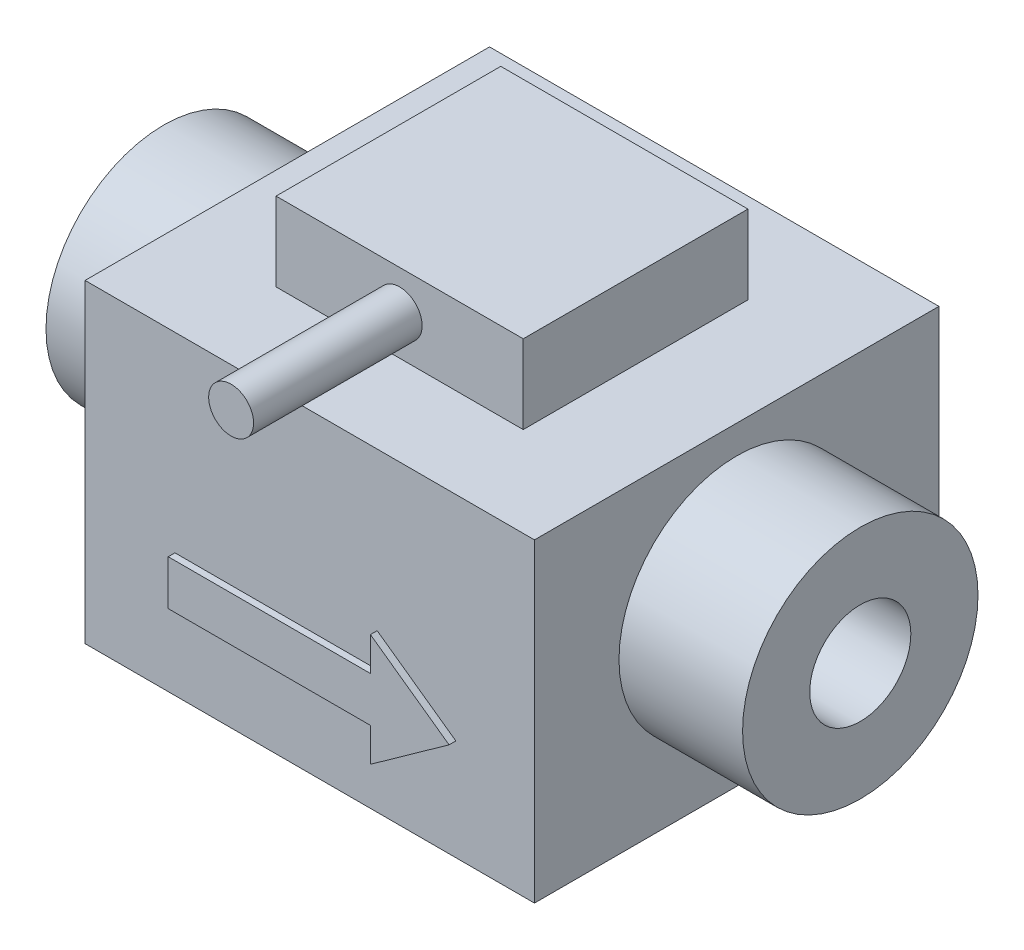
SolidWorks part; units mm, degrees
material "Nylon 6/10"
ref_plane "Front Plane" through (0, 0, 0) normal (0, 0, 1) x (1, 0, 0)
ref_plane "Top Plane" through (0, 0, 0) normal (0, 1, 0) x (1, 0, 0)
ref_plane "Right Plane" through (0, 0, 0) normal (1, 0, 0) x (0, 0, -1)
other "Configuration Table"
sketch "Sketch1" plane through (0, 0, 0) normal (0, 1, 0) x (1, 0, 0)
  line L1 (-20, -18) -> (20, -18)
  line L2 (-20, -18) -> (-20, 18)
  line L3 (-20, 18) -> (20, 18)
  line L4 (20, -18) -> (20, 18)
  line L5 (-20, -18) -> (20, 18) construction
  line L6 (-20, 18) -> (20, -18) construction
  point P6 (0, 0)
  dimension "D1" = 40
  dimension "D2" = 36
extrude "Body" add sketch "Sketch1" along normal blind 28
sketch "Sketch2" plane through (0, 0, 0) normal (0, 1, 0) x (1, 0, 0)
  line L0 (-11, -10) -> (11, -10)
  line L1 (11, -10) -> (11, 10)
  line L2 (11, 10) -> (-11, 10)
  line L3 (-11, 10) -> (-11, -10)
extrude "Sensor_Housing" add sketch "Sketch2" along normal blind 7 from offset 28
sketch "Sketch3" plane through (0, 0, 0) normal (1, 0, 0) x (0, 0, -1)
  circle A0 centre (0, 15) radius 10.4775
  dimension "D1" = 20.955
extrude "Inlet_Thread" add sketch "Sketch3" along normal blind 11 from offset 31
sketch "Sketch4" plane through (0, 0, 0) normal (1, 0, 0) x (0, 0, -1)
  circle A0 centre (0, 15) radius 10.4775
  dimension "D1" = 20.955
extrude "Outlet_Thread" add sketch "Sketch4" along normal blind 11 from offset 20
sketch "Sketch5" plane through (0, 0, 0) normal (1, 0, 0) x (0, 0, -1)
  circle A0 centre (0, 15) radius 4.5
  dimension "D1" = 9
extrude "Inlet_Bore" cut sketch "Sketch5" along normal blind 8 from offset 31
sketch "Sketch6" plane through (0, 0, 0) normal (1, 0, 0) x (0, 0, -1)
  circle A0 centre (0, 15) radius 4.5
  dimension "D1" = 9
extrude "Outlet_Bore" cut sketch "Sketch6" against normal blind 8 from offset 31
sketch "Sketch7" plane through (0, 0, 0) normal (0, 0, 1) x (1, 0, 0)
  circle A0 centre (0, 31.5) radius 2
  dimension "D1" = 4
extrude "Cable_Stub" add sketch "Sketch7" along normal blind 15 from offset 10
sketch "Sketch8" plane through (0, 0, 0) normal (0, 0, 1) x (1, 0, 0)
  line L0 (-12, 7) -> (6, 7)
  line L1 (6, 7) -> (6, 4)
  line L2 (6, 4) -> (13, 9)
  line L3 (13, 9) -> (6, 14)
  line L4 (6, 14) -> (6, 11)
  line L5 (6, 11) -> (-12, 11)
  line L6 (-12, 11) -> (-12, 7)
extrude "Flow_Arrow" add sketch "Sketch8" along normal blind 0.6 from offset 18
equation "\"Jar_OD\"= 90  'ASSUMED - Part G fallback - jar outer diameter"
equation "\"Jar_H\"= 120  'ASSUMED - Part G fallback - jar height"
equation "\"Pump_L\"= 45  'ASSUMED - Part G fallback"
equation "\"Pump_W\"= 24  'ASSUMED - Part G fallback"
equation "\"Pump_H\"= 33  'ASSUMED - Part G fallback"
equation "\"Pump_Outlet_OD\"= 7.5  'ASSUMED - Part G fallback"
equation "\"Tube_OD\"= 8  'ASSUMED - Part G fallback"
equation "\"Tube_ID\"= 6  'ASSUMED - Part G fallback"
equation "\"TDS_Body_Dia\"= 12  'ASSUMED - Part G fallback"
equation "\"TDS_Wet_Len\"= 45  'ASSUMED - Part G fallback - length in water"
equation "\"DS_Tube_Dia\"= 6  'ASSUMED - Part G fallback"
equation "\"DS_Tube_Len\"= 50  'ASSUMED - Part G fallback"
equation "\"ORP_Body_Dia\"= 12  'ASSUMED - Part G fallback"
equation "\"ORP_Body_Len\"= 150  'ASSUMED - Part G fallback"
equation "\"ORP_Cap_Dia\"= 16  'ASSUMED - Part G fallback"
equation "\"Turb_W\"= 33  'ASSUMED - Part G fallback - head width"
equation "\"Turb_D\"= 28  'ASSUMED - Part G fallback - head depth"
equation "\"Turb_H\"= 30  'ASSUMED - Part G fallback - head height"
equation "\"Turb_Slot_W\"= 10  'ASSUMED - Part G fallback - slot width"
equation "\"Flow_L\"= 62  'ASSUMED - Part G fallback YF-S201"
equation "\"Flow_W\"= 36  'ASSUMED - Part G fallback"
equation "\"Flow_H\"= 35  'ASSUMED - Part G fallback"
equation "\"Thread_G12_OD\"= 20.955  'ASSUMED - Part G fallback thread G1/2 (major diameter)"
equation "\"Valve_L\"= 75  'ASSUMED - Part G fallback"
equation "\"Valve_W\"= 45  'ASSUMED - Part G fallback"
equation "\"Valve_H\"= 60  'ASSUMED - Part G fallback"
equation "\"Tee_L\"= 40  'ASSUMED - Part G fallback - overall length"
equation "\"Tee_Branch_L\"= 25  'ASSUMED - Part G fallback"
equation "\"Tee_OD\"= 12  'ASSUMED - Part G fallback"
equation "\"Cuv_W\"= 12.5  'ASSUMED - old R3 cuvette (station suppressed in SS4)"
equation "\"Cuv_D\"= 12.5  'ASSUMED - old R3 cuvette (station suppressed in SS4)"
equation "\"Cuv_H\"= 45  'ASSUMED - old R3 cuvette (station suppressed in SS4)"
equation "\"LED_Board_L\"= 20  'ASSUMED - Part G fallback"
equation "\"LED_Board_W\"= 20  'ASSUMED - Part G fallback - LED at centre"
equation "\"GUVA_L\"= 20  'ASSUMED - Part G fallback"
equation "\"GUVA_W\"= 12  'ASSUMED - Part G fallback - sensor at centre"
equation "\"Reed_L\"= 27  'ASSUMED - Part G fallback MC-38 half"
equation "\"Reed_W\"= 14  'ASSUMED - Part G fallback"
equation "\"Reed_H\"= 8  'ASSUMED - Part G fallback"
equation "\"ESP_L\"= 51  'ASSUMED - Part G fallback"
equation "\"ESP_W\"= 28  'ASSUMED - Part G fallback"
equation "\"TFT_L\"= 58  'ASSUMED - Part G fallback - board"
equation "\"TFT_W\"= 35  'ASSUMED - Part G fallback - board"
equation "\"TFT_Win_L\"= 35  'ASSUMED - Part G fallback - visible window"
equation "\"TFT_Win_W\"= 28  'ASSUMED - Part G fallback - visible window"
equation "\"Relay_L\"= 50  'ASSUMED - Part G fallback"
equation "\"Relay_W\"= 26  'ASSUMED - Part G fallback"
equation "\"Relay_H\"= 19  'ASSUMED - Part G fallback"
equation "\"Mosfet_L\"= 34  'ASSUMED - Part G fallback"
equation "\"Mosfet_W\"= 17  'ASSUMED - Part G fallback"
equation "\"Mosfet_H\"= 12  'ASSUMED - Part G fallback"
equation "\"TDS_Board_L\"= 42  'ASSUMED - Part G fallback"
equation "\"TDS_Board_W\"= 32  'ASSUMED - Part G fallback"
equation "\"Turb_Board_L\"= 38  'ASSUMED - Part G fallback"
equation "\"Turb_Board_W\"= 28  'ASSUMED - Part G fallback"
equation "\"BNC_Thread_Dia\"= 9.5  'ASSUMED - Part G fallback"
equation "\"Plate_L\"= 420  'ASSUMED - Part G fallback"
equation "\"Plate_W\"= 297  'ASSUMED - Part G fallback"
equation "\"Plate_T\"= 6  'ASSUMED - Part G fallback"
equation "\"Probe_Clr\"= 0.3  'DESIGN VALUE - Part C rule 3 - printed probe hole = diameter + 0.3"
equation "\"Cuv_Clr\"= 0.2  'DESIGN VALUE - Part C rule 3 - cuvette pocket = size + 0.2"
equation "\"Label_H\"= 0.6  'DESIGN VALUE - Part D - raised label height"
equation "\"D2@Sketch1\" = \"Flow_W\""
equation "\"D1@Sketch3\" = \"Thread_G12_OD\""
equation "\"D1@Sketch4\" = \"Thread_G12_OD\""
equation "\"Booster_L\"= 150  'ASSUMED - Part G fallback - booster pump"
equation "\"Booster_W\"= 95  'ASSUMED - Part G fallback"
equation "\"Booster_H\"= 100  'ASSUMED - Part G fallback"
equation "\"PTube_OD\"= 6.35  'ASSUMED - Part G fallback - product tube 1/4 inch"
equation "\"Qz_Out\"= 12  'ASSUMED - Part G fallback - quartz channel outside square"
equation "\"Qz_Path\"= 10  'ASSUMED - Part G fallback - quartz channel inside light path"
equation "\"Qz_L\"= 40  'ASSUMED - Part G fallback - quartz channel length"
equation "\"LED860_Dia\"= 5  'ASSUMED - Part G fallback - 860 nm LED"
equation "\"BPW_L\"= 5.4  'ASSUMED - Part G fallback - BPW34"
equation "\"BPW_W\"= 4.3  'ASSUMED - Part G fallback - BPW34"
equation "\"Cart_Dia\"= 50  'ASSUMED - Part G fallback - sediment and pre-carbon cartridges"
equation "\"Cart_L\"= 255  'ASSUMED - Part G fallback"
equation "\"UF_Dia\"= 50  'ASSUMED - Part G fallback - UF cartridge"
equation "\"UF_L\"= 260  'ASSUMED - Part G fallback"
equation "\"RO_Dia\"= 62  'ASSUMED - Part G fallback - RO membrane housing"
equation "\"RO_L\"= 300  'ASSUMED - Part G fallback"
equation "\"UVC_Dia\"= 40  'ASSUMED - Part G fallback - UV-C chamber"
equation "\"UVC_L\"= 300  'ASSUMED - Part G fallback"
equation "\"Tank_W\"= 260  'ASSUMED - Part G fallback - storage tank"
equation "\"Tank_D\"= 160  'ASSUMED - Part G fallback"
equation "\"Tank_H\"= 300  'ASSUMED - Part G fallback"
equation "\"Cab_W\"= 400  'ASSUMED - Part G fallback - purifier cabinet"
equation "\"Cab_D\"= 270  'ASSUMED - Part G fallback"
equation "\"Cab_H\"= 560  'ASSUMED - Part G fallback"
equation "\"ORP_Board_L\"= 40  'ASSUMED - Part G fallback - ORP buffer board"
equation "\"ORP_Board_W\"= 30  'ASSUMED - Part G fallback"
equation "\"Opt_Board_L\"= 50  'ASSUMED - Part G fallback - optical front-end board"
equation "\"Opt_Board_W\"= 40  'ASSUMED - Part G fallback"
equation "\"Buck_L\"= 43  'ASSUMED - Part G fallback - 12 V to 5 V buck module"
equation "\"Buck_W\"= 21  'ASSUMED - Part G fallback"
equation "\"Buck_H\"= 14  'ASSUMED - Part G fallback"
equation "\"BB_L\"= 165  'ASSUMED - Part G fallback - breadboard (As_Built_R3 only)"
equation "\"BB_W\"= 55  'ASSUMED - Part G fallback"
equation "\"BB_H\"= 10  'ASSUMED - Part G fallback"
